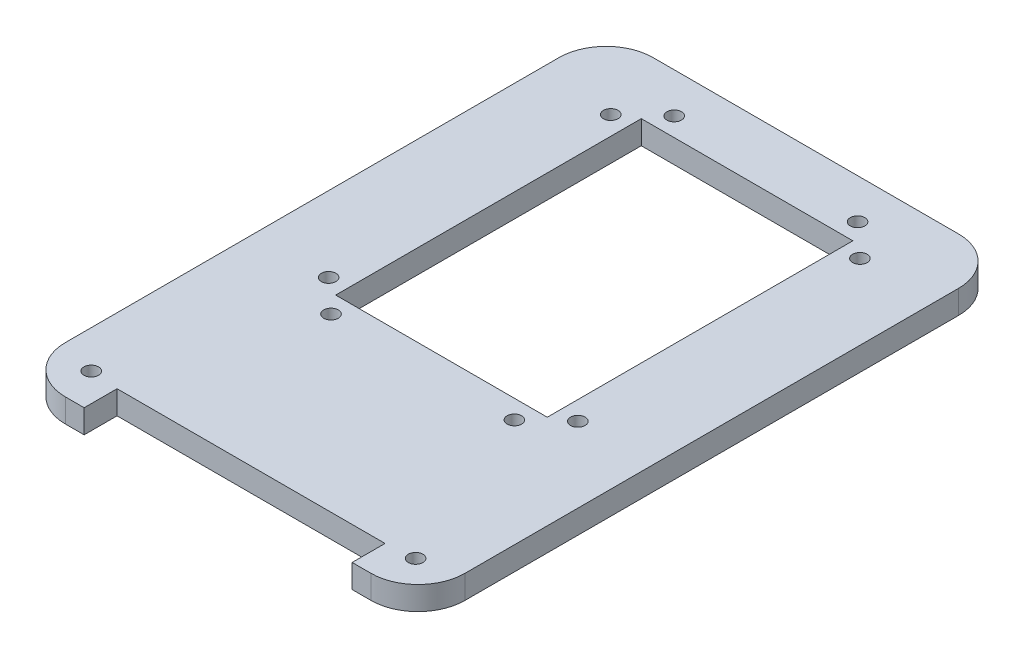
SolidWorks part; units mm, degrees
material "Mahogany"
ref_plane "Front Plane" through (0, 0, 0) normal (0, 0, 1) x (1, 0, 0)
ref_plane "Top Plane" through (0, 0, 0) normal (0, 1, 0) x (1, 0, 0)
ref_plane "Right Plane" through (0, 0, 0) normal (1, 0, 0) x (0, 0, -1)
sketch "Sketch1" plane through (0, 0, 0) normal (0, 1, 0) x (1, 0, 0)
  line L1 (-42.5, -80) -> (42.5, -80)
  line L2 (-42.5, -80) -> (-42.5, 80)
  line L3 (-42.5, 80) -> (42.5, 80)
  line L4 (42.5, -80) -> (42.5, 80)
  line L5 (-42.5, -80) -> (42.5, 80) construction
  line L6 (-42.5, 80) -> (42.5, -80) construction
  point P0 (0, 0)
  dimension "D1" = 160
  dimension "D2" = 85
extrude "Boss-Extrude1" add sketch "Sketch1" along normal blind 5
sketch "Sketch2" plane through (0, 5, 0) normal (0, 1, 0) x (1, 0, 0)
  line L1 (-22.5, -32.5) -> (22.5, -32.5)
  line L2 (-22.5, -32.5) -> (-22.5, 32.5)
  line L3 (-22.5, 32.5) -> (22.5, 32.5)
  line L4 (22.5, -32.5) -> (22.5, 32.5)
  line L5 (-22.5, -32.5) -> (22.5, 32.5) construction
  line L6 (-22.5, 32.5) -> (22.5, -32.5) construction
  point P0 (0, 0)
  dimension "D1" = 45
  dimension "D2" = 65
extrude "Cut-Extrude1" cut sketch "Sketch2" against normal through all
sketch "Sketch8" plane through (0, 5, 0) normal (0, 1, 0) x (1, 0, 0)
  line L0 (-42.5, -80) -> (42.5, -80) construction
  line L1 (-28.5, -87) -> (28.5, -87)
  line L2 (-28.5, -87) -> (-28.5, -73)
  line L3 (-28.5, -73) -> (28.5, -73)
  line L4 (28.5, -87) -> (28.5, -73)
  line L5 (-28.5, -87) -> (28.5, -73) construction
  line L6 (-28.5, -73) -> (28.5, -87) construction
  point P0 (0, -80)
  dimension "D1" = 57
  dimension "D2" = 7
extrude "Cut-Extrude2" cut sketch "Sketch8" against normal through all
sketch "Sketch9" plane through (0, 5, 0) normal (0, 1, 0) x (1, 0, 0)
  line L0 (22.5, 32.5) -> (-22.5, 32.5) construction
  line L1 (22.5, -32.5) -> (22.5, 32.5) construction
  circle A0 centre (26.5, 30) radius 1.5
  dimension "D3" = 3
  dimension "D1" = 2.5
  dimension "D2" = 4
hole_wizard "Ø2.0mm Dowel Hole1" positions "3DSketch1" profile "Sketch10" hole size "Ø2.0" standard "ANSI Metric"
sketch3d "3DSketch1"
  point P0 (26.5, 5, -30)
sketch "Sketch10" plane through (26.5, 5, -30) normal (1, 0, 0) x (0, 0, 1)
  line L0 (0, 0) -> (0, 5.9303)
  line L1 (0, 5.9303) -> (1.55, 4.999)
  line L2 (1.55, 4.999) -> (1.55, 0)
  line L5 (1.55, 0) -> (0, 0)
  line L10 (0, 5.9303) -> (-1.55, 4.999) construction
  line L11 (0, -6.35) -> (0, 107.95) construction
  dimension "Hole Dia." = 3.1
  dimension "Hole Depth" = 4.999
  dimension "Drill Angle" = 118
mirror "Mirror8" about plane through (0, 0, 0) normal (1, 0, 0) of "Ø2.0mm Dowel Hole1"
mirror "Mirror9" about plane through (0, 0, 0) normal (0, 0, 1) of "Mirror8", "Ø2.0mm Dowel Hole1"
sketch "Sketch19" plane through (0, 5, 0) normal (0, 1, 0) x (1, 0, 0)
  line L0 (22.5, 32.5) -> (-22.5, 32.5) construction
  line L1 (22.5, -32.5) -> (22.5, 32.5) construction
  circle A0 centre (19.5, 36.5) radius 1
  dimension "D1" = 2
  dimension "D2" = 4
  dimension "D3" = 3
hole_wizard "Ø2.0mm Dowel Hole3" positions "3DSketch3" profile "Sketch21" hole size "Ø2.0" standard "ANSI Metric"
sketch3d "3DSketch3"
  point P0 (19.5, 5, -36.5)
sketch "Sketch21" plane through (19.5, 5, -36.5) normal (1, 0, 0) x (0, 0, 1)
  line L0 (0, 0) -> (0, 5.9303)
  line L1 (0, 5.9303) -> (1.55, 4.999)
  line L2 (1.55, 4.999) -> (1.55, 0)
  line L5 (1.55, 0) -> (0, 0)
  line L10 (0, 5.9303) -> (-1.55, 4.999) construction
  line L11 (0, -6.35) -> (0, 107.95) construction
  dimension "Hole Dia." = 3.1
  dimension "Hole Depth" = 4.999
  dimension "Drill Angle" = 118
mirror "Mirror10" about plane through (0, 0, 0) normal (1, 0, 0) of "Ø2.0mm Dowel Hole3"
mirror "Mirror11" about plane through (0, 0, 0) normal (0, 0, 1) of "Ø2.0mm Dowel Hole3", "Mirror10"
sketch "Sketch36" plane through (0, 5, 0) normal (0, 1, 0) x (1, 0, 0)
  line L0 (28.5, -80) -> (28.5, -73) construction
  line L1 (28.5, -80) -> (42.5, -80) construction
  circle A0 centre (34.5, -72.5) radius 1.5
  dimension "D3" = 3
  dimension "D1" = 6
  dimension "D2" = 7.5
hole_wizard "Ø2.5mm Dowel Hole4" positions "3DSketch5" profile "Sketch38" hole size "Ø2.5" standard "ANSI Metric"
sketch3d "3DSketch5"
  point P0 (34.5, 5, 72.5)
sketch "Sketch38" plane through (34.5, 5, 72.5) normal (1, 0, 0) x (0, 0, 1)
  line L0 (0, 0) -> (0, 5.9303)
  line L1 (0, 5.9303) -> (1.55, 4.999)
  line L2 (1.55, 4.999) -> (1.55, 0)
  line L5 (1.55, 0) -> (0, 0)
  line L10 (0, 5.9303) -> (-1.55, 4.999) construction
  line L11 (0, -6.35) -> (0, 107.95) construction
  dimension "Hole Dia." = 3.1
  dimension "Hole Depth" = 4.999
  dimension "Drill Angle" = 118
mirror "Mirror12" about plane through (0, 0, 0) normal (1, 0, 0) of "Ø2.5mm Dowel Hole4"
sketch "Sketch39" plane through (0, 0, -80) normal (0, 0, -1) x (-1, 0, 0)
  line L1 (42.5, 5) -> (-42.5, 5)
  line L2 (42.5, 5) -> (42.5, 0)
  line L3 (42.5, 0) -> (-42.5, 0)
  line L4 (-42.5, 5) -> (-42.5, 0)
extrude "Cut-Extrude3" cut sketch "Sketch39" against normal blind 35
fillet "Fillet1" radius 10 4 edges at (42.5, 2.5, 80) (-42.5, 2.5, 80) (-42.5, 2.5, -45) (42.5, 2.5, -45)
sketch "Sketch41" plane through (0, 0, 0) normal (0, -1, 0) x (-1, 0, 0)
  line L0 (28.5, -73) -> (28.5, -80) construction
  line L1 (23.5, -63) -> (-23.5, -63)
  line L2 (23.5, -63) -> (23.5, -48)
  line L3 (23.5, -48) -> (-23.5, -48)
  line L4 (-23.5, -63) -> (-23.5, -48)
  line L5 (-28.5, -73) -> (-28.5, -80) construction
  line L6 (-28.5, -73) -> (28.5, -73) construction
  line L7 (22.5, -32.5) -> (-22.5, -32.5) construction
  line L8 (-22.5, 32.5) -> (22.5, 32.5) construction
  line L9 (37.5, -22.5) -> (27.5, -22.5)
  line L10 (37.5, -22.5) -> (37.5, 22.5)
  line L11 (37.5, 22.5) -> (27.5, 22.5)
  line L12 (27.5, -22.5) -> (27.5, 22.5)
  line L13 (-27.5, -22.5) -> (-37.5, -22.5)
  line L14 (-27.5, -22.5) -> (-27.5, 22.5)
  line L15 (-27.5, 22.5) -> (-37.5, 22.5)
  line L16 (-37.5, -22.5) -> (-37.5, 22.5)
  line L17 (-22.5, -32.5) -> (-22.5, 32.5) construction
  line L21 (42.5, 35) -> (42.5, -70) construction
  point P30 (42.5, -22.5)
  dimension "D1" = 5
  dimension "D2" = 5
  dimension "D3" = 10
  dimension "D4" = 15
  dimension "D5" = 10
  dimension "D6" = 10
  dimension "D7" = 10
  dimension "D8" = 10
  dimension "D9" = 10
  dimension "D10" = 5
  dimension "D11" = 10
  dimension "D12" = 5
extrude "Boss-Extrude3" add sketch "Sketch41" along normal blind 4.5
equation "\"D4\"=15"
